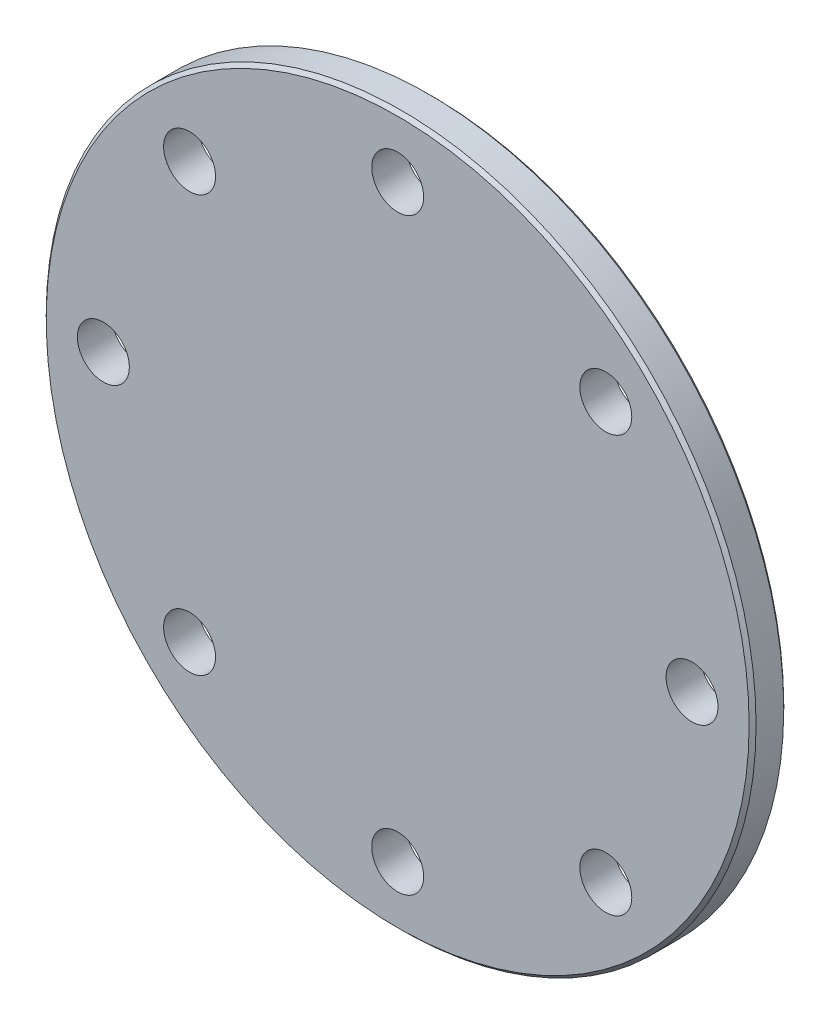
SolidWorks part; units mm, degrees
material "1023 Carbon Steel Sheet (SS)"
ref_plane "Front Plane" through (0, 0, 0) normal (0, 0, 1) x (1, 0, 0)
ref_plane "Top Plane" through (0, 0, 0) normal (0, 1, 0) x (1, 0, 0)
ref_plane "Right Plane" through (0, 0, 0) normal (1, 0, 0) x (0, 0, -1)
sketch "Sketch1" plane through (0, 0, 0) normal (0, 0, 1) x (1, 0, 0)
  circle A0 centre (0, 0) radius 205
  circle A1 centre (0, 170) radius 15
  circle A2 centre (120.2082, 120.2082) radius 15
  circle A3 centre (170, 0) radius 15
  circle A4 centre (120.2082, -120.2082) radius 15
  circle A5 centre (0, -170) radius 15
  circle A6 centre (-120.2082, -120.2082) radius 15
  circle A7 centre (-170, 0) radius 15
  circle A8 centre (-120.2082, 120.2082) radius 15
  point P22 (0, 0)
  dimension "D1" = 170
  dimension "D2" = 30
  dimension "D4" = 410
  dimension "D3" = 8
extrude "Boss-Extrude1" add sketch "Sketch1" along normal blind 20 contours A0
chamfer "Chamfer1" distance 2 angle 45 2 edges at (205, 0, 0) (205, 0, 20)
